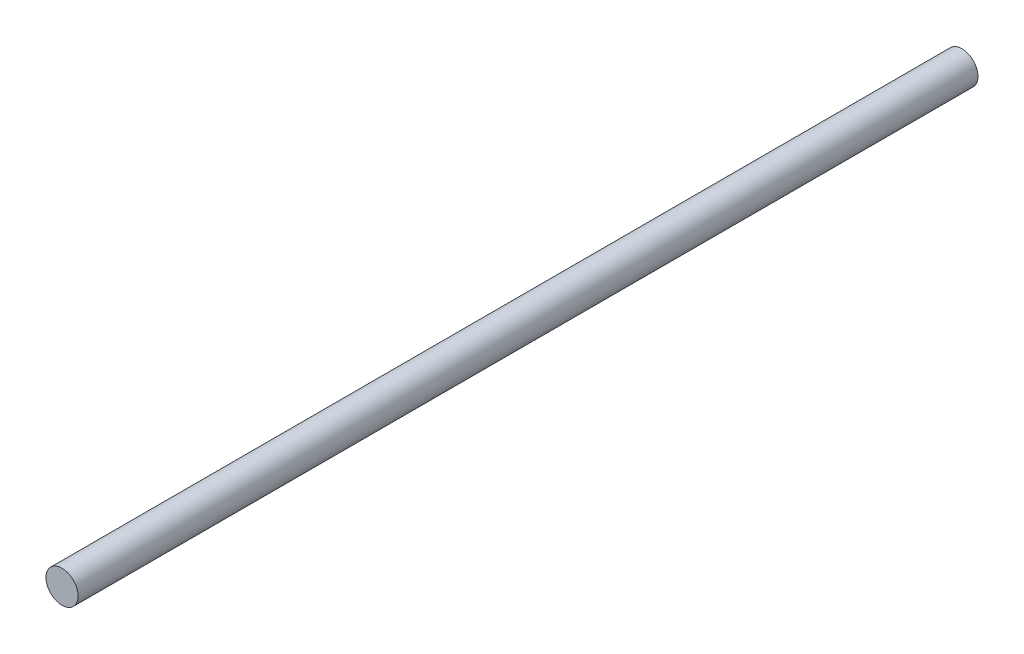
SolidWorks part; units mm, degrees
ref_plane "Front Plane" through (0, 0, 0) normal (0, 0, 1) x (1, 0, 0)
ref_plane "Top Plane" through (0, 0, 0) normal (0, 1, 0) x (1, 0, 0)
ref_plane "Right Plane" through (0, 0, 0) normal (1, 0, 0) x (0, 0, -1)
sketch "Sketch1" plane through (0, 0, 0) normal (0, 0, 1) x (1, 0, 0)
  circle A0 centre (0, 0) radius 4
extrude "Boss-Extrude1" add sketch "Sketch1" along normal mid plane 224
